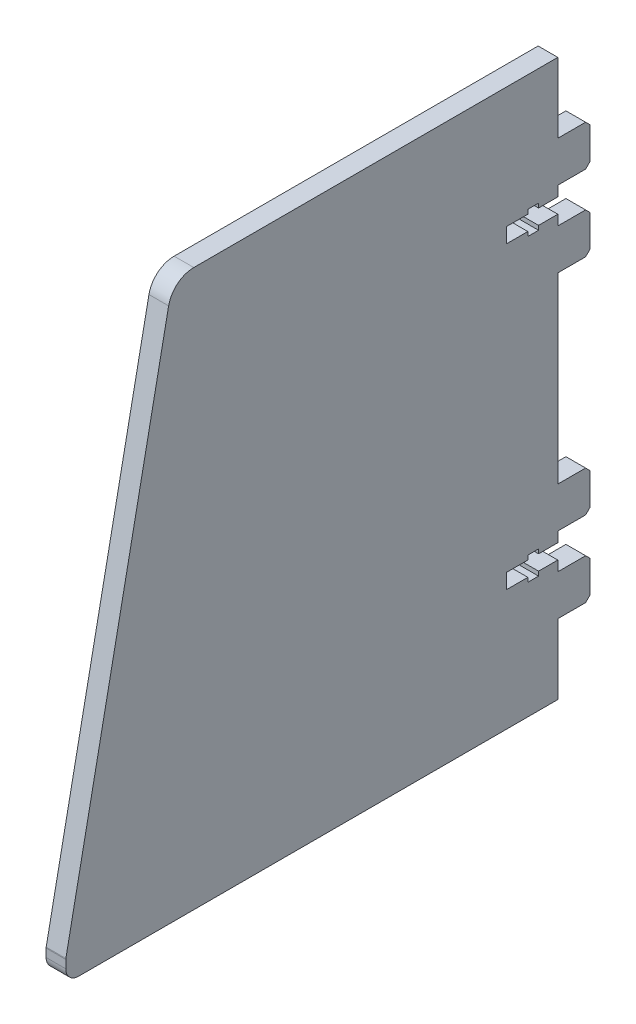
SolidWorks part; units mm, degrees
ref_plane "Front Plane" through (0, 0, 0) normal (0, 0, 1) x (1, 0, 0)
ref_plane "Top Plane" through (0, 0, 0) normal (0, 1, 0) x (1, 0, 0)
ref_plane "Right Plane" through (0, 0, 0) normal (1, 0, 0) x (0, 0, -1)
sketch "Sketch1" plane through (0, 0, 0) normal (1, 0, 0) x (0, 0, -1)
  line L0 (120.0679, 91.2675) -> (126.5679, 91.2675)
  line L1 (126.5679, 91.2675) -> (127.5679, 92.2675)
  line L2 (127.5679, 92.2675) -> (127.5679, 99.7675)
  line L3 (127.5679, 99.7675) -> (126.5679, 100.7675)
  line L4 (126.5679, 100.7675) -> (120.0679, 100.7675)
  line L5 (120.0679, 100.7675) -> (120.0679, 103.1425)
  line L6 (120.0679, 103.1425) -> (115.5679, 103.1425)
  line L7 (115.5679, 103.1425) -> (115.5679, 102.1425)
  line L8 (115.5679, 102.1425) -> (113.0679, 102.1425)
  line L9 (113.0679, 102.1425) -> (113.0679, 103.1425)
  line L10 (113.0679, 103.1425) -> (108.0679, 103.1425)
  line L11 (108.0679, 103.1425) -> (108.0679, 106.6425)
  line L12 (108.0679, 106.6425) -> (113.0679, 106.6425)
  line L13 (113.0679, 106.6425) -> (113.0679, 107.6425)
  line L14 (113.0679, 107.6425) -> (115.5679, 107.6425)
  line L15 (115.5679, 107.6425) -> (115.5679, 106.6425)
  line L16 (115.5679, 106.6425) -> (120.0679, 106.6425)
  line L17 (120.0679, 106.6425) -> (120.0679, 109.0175)
  line L18 (120.0679, 109.0175) -> (126.5679, 109.0175)
  line L19 (126.5679, 109.0175) -> (127.5679, 110.0175)
  line L20 (127.5679, 110.0175) -> (127.5679, 117.5175)
  line L21 (127.5679, 117.5175) -> (126.5679, 118.5175)
  line L22 (126.5679, 118.5175) -> (120.0679, 118.5175)
  line L23 (120.0679, 118.5175) -> (120.0679, 134.8925)
  line L24 (120.0679, 134.8925) -> (34.9867, 134.8925)
  line L25 (29.1033, 130.0692) -> (5.0873, 9.9896)
  line L26 (5.0679, 9.7935) -> (5.0679, 7.8925)
  line L27 (8.0679, 4.8925) -> (120.0679, 4.8925)
  line L28 (120.0679, 4.8925) -> (120.0679, 21.2675)
  line L29 (120.0679, 21.2675) -> (126.5679, 21.2675)
  line L30 (126.5679, 21.2675) -> (127.5679, 22.2675)
  line L31 (127.5679, 22.2675) -> (127.5679, 29.7675)
  line L32 (127.5679, 29.7675) -> (126.5679, 30.7675)
  line L33 (126.5679, 30.7675) -> (120.0679, 30.7675)
  line L34 (120.0679, 30.7675) -> (120.0679, 33.1425)
  line L35 (120.0679, 33.1425) -> (115.5679, 33.1425)
  line L36 (115.5679, 33.1425) -> (115.5679, 32.1425)
  line L37 (115.5679, 32.1425) -> (113.0679, 32.1425)
  line L38 (113.0679, 32.1425) -> (113.0679, 33.1425)
  line L39 (113.0679, 33.1425) -> (108.0679, 33.1425)
  line L40 (108.0679, 33.1425) -> (108.0679, 36.6425)
  line L41 (108.0679, 36.6425) -> (113.0679, 36.6425)
  line L42 (113.0679, 36.6425) -> (113.0679, 37.6425)
  line L43 (113.0679, 37.6425) -> (115.5679, 37.6425)
  line L44 (115.5679, 37.6425) -> (115.5679, 36.6425)
  line L45 (115.5679, 36.6425) -> (120.0679, 36.6425)
  line L46 (120.0679, 36.6425) -> (120.0679, 39.0175)
  line L47 (120.0679, 39.0175) -> (126.5679, 39.0175)
  line L48 (126.5679, 39.0175) -> (127.5679, 40.0175)
  line L49 (127.5679, 40.0175) -> (127.5679, 47.5175)
  line L50 (127.5679, 47.5175) -> (126.5679, 48.5175)
  line L51 (126.5679, 48.5175) -> (120.0679, 48.5175)
  line L52 (120.0679, 48.5175) -> (120.0679, 91.2675)
  arc A0 (34.9867, 134.8925) -> (29.1033, 130.0692) centre (34.9867, 128.8925) ccw
  arc A1 (5.0873, 9.9896) -> (5.0679, 9.7935) centre (6.0679, 9.7935) ccw
  arc A2 (5.0679, 7.8925) -> (8.0679, 4.8925) centre (8.0679, 7.8925) ccw
extrude "Extrude1" add sketch "Sketch1" along normal blind 4.6
sketch "Sketch2" plane through (0, 0, -108.0679) normal (0, 0, -1) x (-1, 0, 0)
  line L0 (0, 106.6425) -> (-4.6, 103.1425)
  line L1 (0, 33.1425) -> (-4.6, 36.6425)
  circle A0 centre (-2.3, 34.8925) radius 1
  circle A1 centre (-2.3, 104.8925) radius 1
  dimension "D1" = 2
  dimension "D2" = 2
extrude "Extrude2" cut sketch "Sketch2" against normal blind 1 contours A0 | A1
